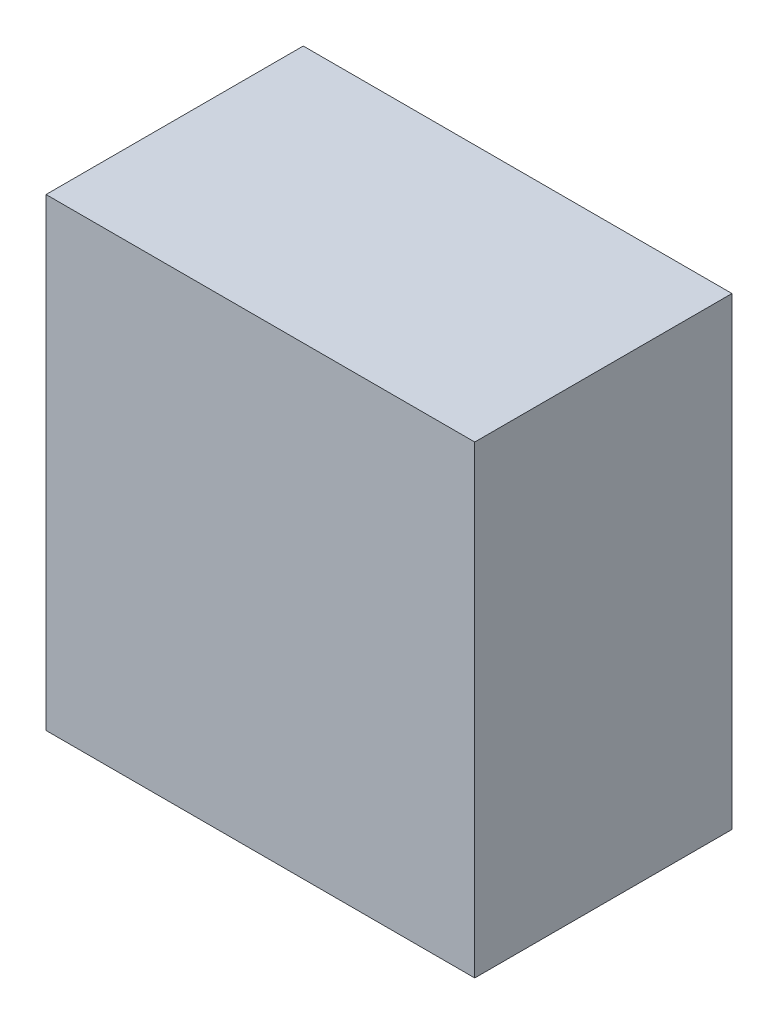
SolidWorks part; units mm, degrees
ref_plane "Front Plane" through (0, 0, 0) normal (0, 0, 1) x (1, 0, 0)
ref_plane "Top Plane" through (0, 0, 0) normal (0, 1, 0) x (1, 0, 0)
ref_plane "Right Plane" through (0, 0, 0) normal (1, 0, 0) x (0, 0, -1)
sketch "Sketch1" plane through (0, 0, 0) normal (0, 0, 1) x (1, 0, 0)
  line L1 (305, -52.21) -> (160, -52.21)
  line L2 (305, -52.21) -> (305, 104.79)
  line L3 (305, 104.79) -> (160, 104.79)
  line L4 (160, -52.21) -> (160, 104.79)
  dimension "D1" = 157
  dimension "D2" = 145
extrude "Boss-Extrude1" add sketch "Sketch1" along normal blind 87
